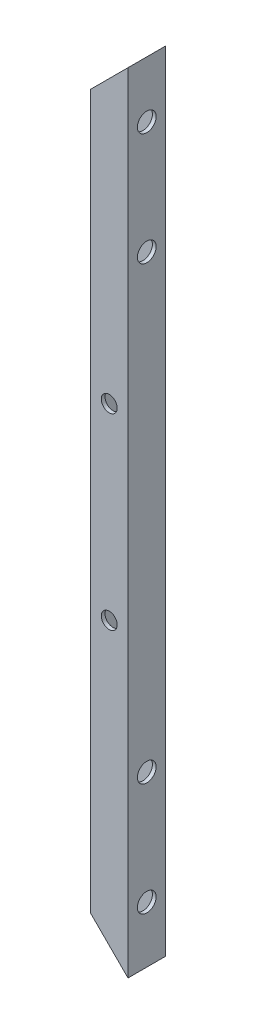
SolidWorks part; units mm, degrees
ref_plane "前视基准面" through (0, 0, 0) normal (0, 0, 1) x (1, 0, 0)
ref_plane "上视基准面" through (0, 0, 0) normal (0, 1, 0) x (1, 0, 0)
ref_plane "右视基准面" through (0, 0, 0) normal (1, 0, 0) x (0, 0, -1)
sketch "草图1" plane through (0, 0, 0) normal (0, 1, 0) x (1, 0, 0)
  line L1 (-5, 5) -> (5, 5)
  line L2 (-5, 5) -> (-5, -5)
  line L3 (-5, -5) -> (5, -5)
  line L4 (5, 5) -> (5, -5)
  line L5 (0, -5) -> (0, 5) construction
  line L6 (-5, 0) -> (5, 0) construction
  line L7 (-4, 4) -> (4, 4)
  line L8 (-4, 4) -> (-4, -4)
  line L9 (-4, -4) -> (4, -4)
  line L10 (4, 4) -> (4, -4)
  line L11 (0, -4) -> (0, 4) construction
  line L12 (-4, 0) -> (4, 0) construction
  point P0 (0, 0)
  point P4 (0, 0)
  dimension "D1" = 10
  dimension "D2" = 10
  dimension "D3" = 1
  dimension "D4" = 1
extrude "凸台-拉伸1" add sketch "草图1" along normal blind 210
sketch "草图2" plane through (5, 0, 0) normal (1, 0, 0) x (0, 0, -1)
  line L0 (0, 210) -> (0, 0) construction
  line L1 (-5, 210) -> (5, 210) construction
  line L2 (-5, 105) -> (5, 105) construction
  line L3 (-5, 210) -> (-5, 0) construction
  line L4 (5, 210) -> (5, 0) construction
  line L5 (0, 132.2236) -> (0, 77.7764) construction
  line L6 (0, 77.7764) -> (54.4472, 77.7764) construction
  line L7 (54.4472, 77.7764) -> (54.4472, 132.2236) construction
  line L8 (54.4472, 132.2236) -> (0, 132.2236) construction
  line L9 (0, 132.2236) -> (54.4472, 77.7764) construction
  circle A0 centre (0, 132.2236) radius 2.5
  circle A1 centre (0, 77.7764) radius 2.5
  dimension "D1" = 5
  dimension "D2" = 45
  dimension "D3" = 77
extrude "切除-拉伸1" [suppressed] cut sketch "草图2" against normal blind 100
sketch "草图4" plane through (0, 0, -5) normal (0, 0, -1) x (-1, 0, 0)
  line L0 (-5, 210) -> (5, 200)
  line L1 (5, 210) -> (5, 0) construction
  line L2 (5, 200) -> (5, 210)
  line L3 (5, 210) -> (-5, 210)
  line L4 (5, 105) -> (-5, 105) construction
  line L5 (-5, 210) -> (-5, 0) construction
  line L6 (5, 0) -> (-5, 0)
  line L7 (5, 10) -> (5, 0)
  line L8 (-5, 0) -> (5, 10)
  dimension "D1" = 45
extrude "切除-拉伸3" cut sketch "草图4" against normal blind 10
sketch "草图5" plane through (-5, 0, 0) normal (-1, 0, 0) x (0, 0, 1)
  line L0 (0, 210) -> (0, 0) construction
  line L1 (5, 210) -> (-5, 210) construction
  line L2 (5, 0) -> (-5, 0) construction
  line L3 (5, 105) -> (-5, 105) construction
  line L4 (5, 200) -> (5, 10) construction
  line L5 (-5, 200) -> (-5, 10) construction
  circle A0 centre (0, 165) radius 2.5
  circle A1 centre (0, 45) radius 2.5
  circle A2 centre (0, 195) radius 2.5
  circle A3 centre (0, 15) radius 2.5
  dimension "D1" = 60
  dimension "D2" = 90
  dimension "D3" = 5
  dimension "D4" = 5
extrude "切除-拉伸4" cut sketch "草图5" against normal blind 10
sketch "草图9" plane through (5, 0, 0) normal (1, 0, 0) x (0, 0, -1)
  line L0 (0, 165) -> (0, 45) construction
  line L1 (-24.2502, 105) -> (38.102, 105) construction
sketch "草图11" plane through (0, 0, 5) normal (0, 0, 1) x (1, 0, 0)
  line L0 (5, 105) -> (-33.4546, 105) construction
  line L1 (5, 165) -> (5, 45) construction
  line L2 (0, 213.1376) -> (0, -8.4126) construction
  line L3 (0, -8.4126) -> (-11.7994, -8.4126) construction
  circle A0 centre (0, 130) radius 2.125
  circle A1 centre (0, 80) radius 2.125
  dimension "D1" = 4.25
  dimension "D2" = 50
extrude "切除-拉伸6" cut sketch "草图11" against normal blind 10
